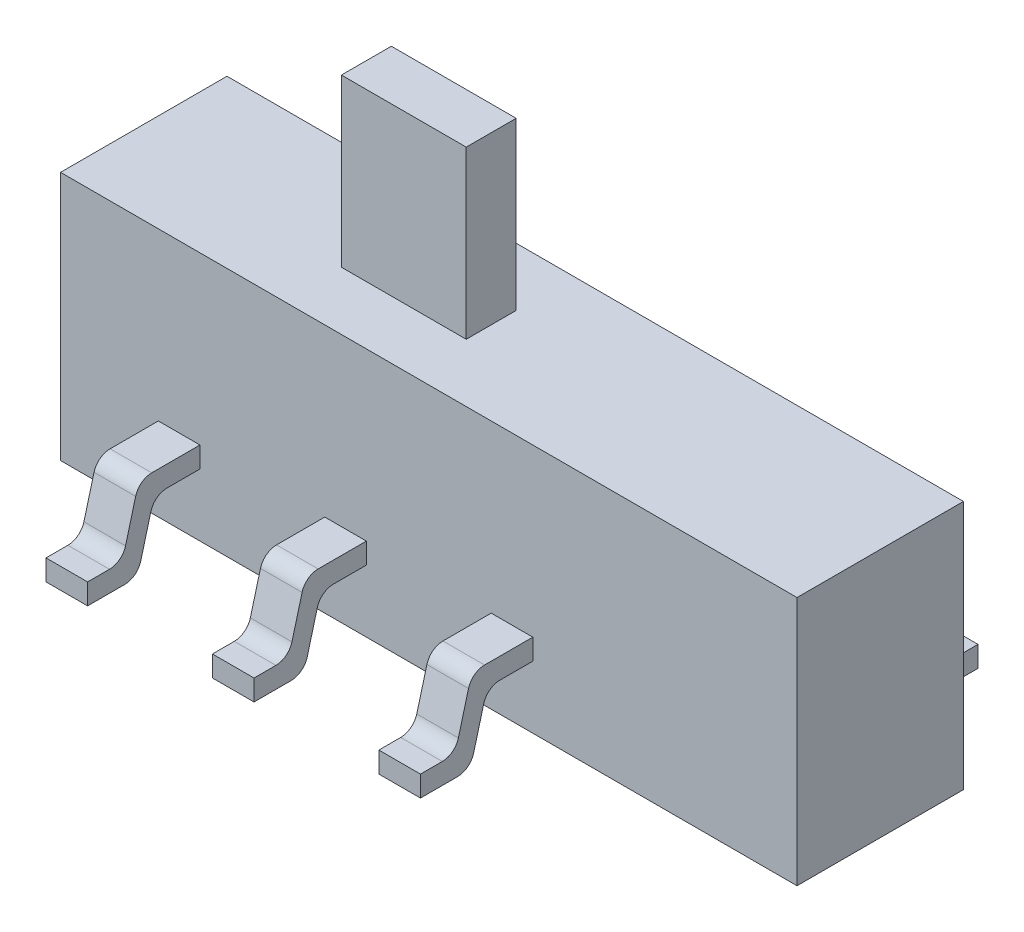
SolidWorks part; units mm, degrees
other "Pin C2"
other "Pin A2"
other "Pin A1"
other "Pin C1"
ref_plane "Front Plane" through (0, 0, 0) normal (0, 0, 1) x (1, 0, 0)
ref_plane "Top Plane" through (0, 0, 0) normal (0, 1, 0) x (1, 0, 0)
ref_plane "Right Plane" through (0, 0, 0) normal (1, 0, 0) x (0, 0, -1)
other "Configuration Table"
sketch "Sketch1" plane through (0, 0, 0) normal (0, 1, 0) x (1, 0, 0)
  line L1 (-4.425, -1) -> (4.425, -1)
  line L2 (-4.425, -1) -> (-4.425, 1)
  line L3 (-4.425, 1) -> (4.425, 1)
  line L4 (4.425, -1) -> (4.425, 1)
  line L5 (-4.425, -1) -> (4.425, 1) construction
  line L6 (-4.425, 1) -> (4.425, -1) construction
  point P0 (0, 0)
  dimension "D1" = 8.85
  dimension "D2" = 2
extrude "Body" add sketch "Sketch1" along normal blind 3
sketch "Sketch2" plane through (0, 3, 0) normal (0, 1, 0) x (1, 0, 0)
  line L1 (-1.75, -0.3) -> (-0.25, -0.3)
  line L2 (-1.75, -0.3) -> (-1.75, 0.3)
  line L3 (-1.75, 0.3) -> (-0.25, 0.3)
  line L4 (-0.25, -0.3) -> (-0.25, 0.3)
  line L5 (-1.75, -0.3) -> (-0.25, 0.3) construction
  line L6 (-1.75, 0.3) -> (-0.25, -0.3) construction
  point P0 (-1, 0)
  point P5 (0, 0)
  dimension "D1" = 1.5
  dimension "D2" = 0.6
  dimension "D3" = 1
extrude "Switch" add sketch "Sketch2" along normal blind 2 separate body
ref_plane "Plane1" through (-1, 0, 0) normal (1, 0, 0) x (0, 0, -1)
sketch "Sketch3" plane through (-1, 0, 0) normal (1, 0, 0) x (0, 0, -1)
  line L0 (-2.35, 0) -> (-1.9044, 0)
  line L1 (-1.7112, 0.1482) -> (-1.5897, 0.6018)
  line L2 (-1.3965, 0.75) -> (-1, 0.75)
  line L3 (-1, 3) -> (-1, 0) construction
  line L4 (-2.35, 0) -> (-2.35, 0.25)
  line L5 (-2.35, 0.25) -> (-2.0874, 0.25)
  line L6 (-1.8943, 0.3982) -> (-1.7727, 0.8518)
  line L7 (-1.5795, 1) -> (-1, 1)
  line L8 (-1, 1) -> (-1, 0.75)
  line L9 (-1.934, 0.25) -> (-1.684, 0.25) construction
  arc A0 (-1.7112, 0.1482) -> (-1.9044, 0) centre (-1.9044, 0.2) cw
  arc A1 (-2.0874, 0.25) -> (-1.8943, 0.3982) centre (-2.0874, 0.45) ccw
  arc A2 (-1.7727, 0.8518) -> (-1.5795, 1) centre (-1.5795, 0.8) cw
  arc A3 (-1.5897, 0.6018) -> (-1.3965, 0.75) centre (-1.3965, 0.55) cw
  point P8 (-1.9, 0.25)
  point P12 (-1.8864, 0.25)
  point P23 (-1.55, 0.75)
  dimension "D6" = 0.2
  dimension "D1" = 1.35
  dimension "D2" = 0.25
  dimension "D3" = 0.55
  dimension "D4" = 1
  dimension "D5" = 75
extrude "Pin B" add sketch "Sketch3" along normal mid plane 0.5 separate body
pattern_linear "LPattern1" count 2 spacing 2 along (1, 0, 0) count 2 spacing 2 along (-1, 0, 0) of bodies 104
mirror "Mirror1" about plane through (0, 0, 0) normal (0, 0, 1) of bodies 106
pattern_linear "LPattern2" count 2 spacing 6 along (1, 0, 0) of bodies 107
